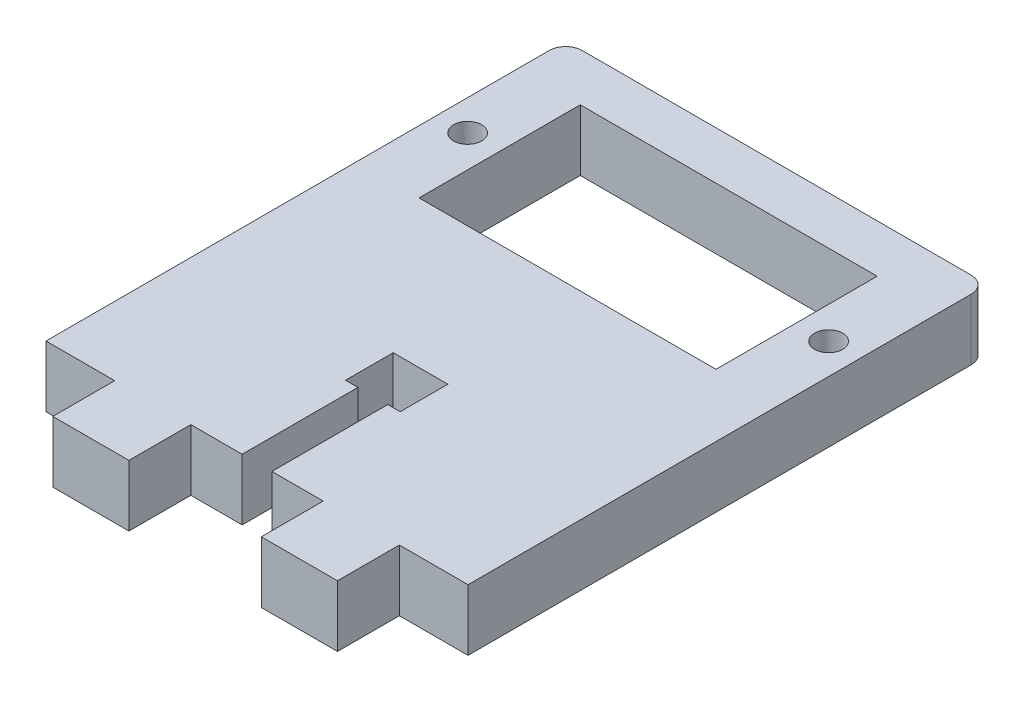
SolidWorks part; units mm, degrees
material "Custom Plastic"
ref_plane "Front Plane" through (0, 0, 0) normal (0, 0, 1) x (1, 0, 0)
ref_plane "Top Plane" through (0, 0, 0) normal (0, 1, 0) x (1, 0, 0)
ref_plane "Right Plane" through (0, 0, 0) normal (1, 0, 0) x (0, 0, -1)
sketch "Sketch1" plane through (0, 0, 0) normal (0, 1, 0) x (1, 0, 0)
  line L0 (-16.1925, 10.0711) -> (16.1925, 10.0711) construction
  line L1 (-16.1925, -19.939) -> (16.1925, -19.939)
  line L2 (-16.1925, -19.939) -> (-16.1925, 19.939)
  line L3 (-16.1925, 19.939) -> (16.1925, 19.939)
  line L4 (16.1925, -19.939) -> (16.1925, 19.939)
  line L5 (-16.1925, -19.939) -> (16.1925, 19.939) construction
  line L6 (-16.1925, 19.939) -> (16.1925, -19.939) construction
  line L7 (0, 0) -> (0, 10.0711) construction
  line L8 (5.08, -24.6888) -> (-5.08, -24.6888) construction
  line L9 (-11.3919, 3.8862) -> (11.3919, 3.8862)
  line L10 (-11.3919, 3.8862) -> (-11.3919, 16.256)
  line L11 (-11.3919, 16.256) -> (11.3919, 16.256)
  line L12 (11.3919, 3.8862) -> (11.3919, 16.256)
  line L13 (-11.3919, 3.8862) -> (11.3919, 16.256) construction
  line L14 (-11.3919, 16.256) -> (11.3919, 3.8862) construction
  line L15 (-10.922, -19.939) -> (-5.08, -19.939)
  line L16 (-10.922, -19.939) -> (-10.922, -24.6888)
  line L17 (-10.922, -24.6888) -> (-5.08, -24.6888)
  line L18 (-5.08, -19.939) -> (-5.08, -24.6888)
  line L19 (10.922, -19.939) -> (5.08, -19.939)
  line L20 (10.922, -19.939) -> (10.922, -24.6888)
  line L21 (10.922, -24.6888) -> (5.08, -24.6888)
  line L22 (5.08, -19.939) -> (5.08, -24.6888)
  line L23 (0, -19.939) -> (0, -24.6888) construction
  point P0 (0, 0)
  dimension "D1" = 32.385
  dimension "D2" = 39.878
  dimension "D3" = 22.7838
  dimension "D4" = 12.3698
  dimension "D5" = 3.683
  dimension "D6" = 21.844
  dimension "D7" = 5.842
  dimension "D8" = 44.6278
extrude "Boss-Extrude1" add sketch "Sketch1" along normal blind 4.699 contours L9 L12 L11 L10 | L18 L1 L16 L17 | L1 L22 L21 L20
sketch "Sketch2" plane through (0, 4.699, 0) normal (0, 1, 0) x (1, 0, 0)
  line L0 (-5.08, -19.939) -> (5.08, -19.939) construction
  line L2 (-1.143, -19.939) -> (-1.143, -11.049)
  line L3 (-1.143, -11.049) -> (1.143, -11.049)
  line L4 (1.143, -19.939) -> (1.143, -11.049)
  line L5 (0, -19.939) -> (0, -11.049) construction
  line L6 (-1.143, -19.939) -> (1.143, -19.939)
  line L7 (-2.0955, -7.3914) -> (2.0955, -7.3914)
  line L8 (-2.0955, -7.3914) -> (-2.0955, -11.049)
  line L9 (-2.0955, -11.049) -> (2.0955, -11.049)
  line L10 (2.0955, -7.3914) -> (2.0955, -11.049)
  line L11 (-11.3919, 3.8862) -> (11.3919, 3.8862) construction
  point P14 (0, -10.2384)
  line M11 (-5.08, -19.939) -> (5.08, -19.939)
  dimension "D1" = 2.286
  dimension "D2" = 4.191
  dimension "D3" = 11.2776
  dimension "D4" = 8.89
extrude "Cut-Extrude1" cut sketch "Sketch2" against normal through all contours L10 L7 L8 L9 L3 | L5 L6 L4 L9 | L5 L3 L2 M11
fillet "Fillet1" radius 1.27 2 edges at (16.1925, 2.3495, -19.939) (-16.1925, 2.3495, -19.939)
sketch "Sketch3" plane through (0, 4.699, 0) normal (0, 1, 0) x (1, 0, 0)
  line L0 (-11.3919, 10.0711) -> (11.3919, 10.0711) construction
  line L1 (-11.3919, 3.8862) -> (-11.3919, 16.256) construction
  line L2 (11.3919, 3.8862) -> (11.3919, 16.256) construction
  line L3 (-11.3919, 10.0711) -> (-13.8506, 10.0711) construction
  line L4 (11.3919, 10.0711) -> (13.8506, 10.0711) construction
  circle A0 centre (-13.8506, 10.0711) radius 1.0795
  circle A1 centre (13.8506, 10.0711) radius 1.0795
  dimension "D2" = 2.159
  dimension "D1" = 27.7012
extrude "Cut-Extrude2" cut sketch "Sketch3" against normal through all contours A1 | A0
